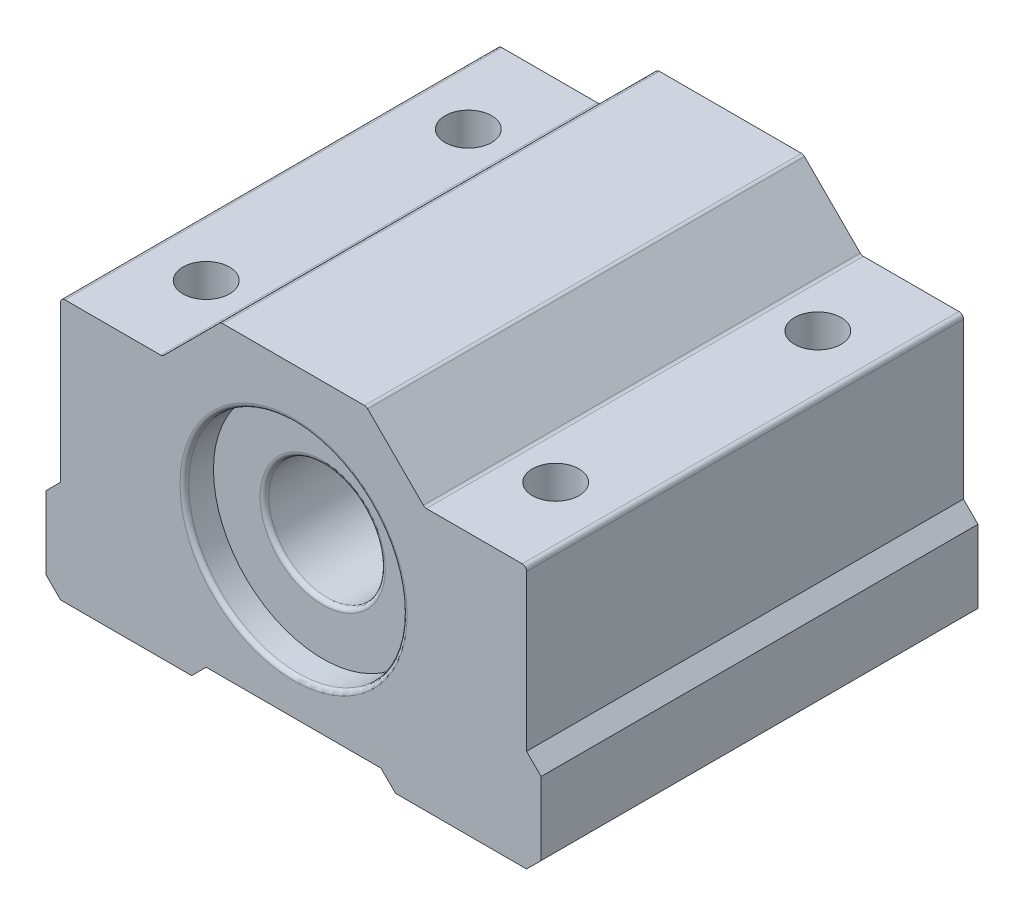
SolidWorks part; units mm, degrees
ref_plane "Front Plane" through (0, 0, 0) normal (0, 0, 1) x (1, 0, 0)
ref_plane "Top Plane" through (0, 0, 0) normal (0, 1, 0) x (1, 0, 0)
ref_plane "Right Plane" through (0, 0, 0) normal (1, 0, 0) x (0, 0, -1)
sketch "Sketch2" plane through (0, 0, 0) normal (0, 0, 1) x (1, 0, 0)
  line L0 (0, 22) -> (0, 0) construction
  line L1 (6, 1) -> (-6, 1)
  line L2 (-6, 1) -> (-7, 0)
  line L3 (6, 1) -> (7, 0)
  line L4 (-7, 0) -> (-17, 0)
  line L5 (7, 0) -> (17, 0)
  line L6 (-17, 0) -> (-17, 6)
  line L7 (17, 0) -> (17, 6)
  line L8 (-17, 6) -> (-16, 7)
  line L9 (17, 6) -> (16, 7)
  line L10 (-16, 7) -> (-16, 18)
  line L11 (16, 7) -> (16, 18)
  line L12 (-16, 18) -> (-9, 18)
  line L13 (16, 18) -> (9, 18)
  line L14 (-9, 18) -> (-5, 22)
  line L15 (9, 18) -> (5, 22)
  line L16 (-5, 22) -> (5, 22)
  circle A0 centre (0, 11) radius 4
  point P6 (0, 1)
  point P20 (0, 22)
  dimension "D10" = 8
  dimension "D1" = 14
  dimension "D2" = 12
  dimension "D3" = 34
  dimension "D4" = 6
  dimension "D5" = 7
  dimension "D6" = 18
  dimension "D7" = 32
  dimension "D8" = 22
  dimension "D9" = 10
  dimension "D11" = 11
extrude "Boss-Extrude1" add sketch "Sketch2" along normal mid plane 30
sketch "Sketch3" plane through (0, 0, -15) normal (0, 0, -1) x (-1, 0, 0)
  circle A0 centre (0, 11) radius 7.5
  dimension "D1" = 15
extrude "Cut-Extrude1" cut sketch "Sketch3" against normal blind 2
mirror "Mirror1" about plane through (0, 0, 0) normal (0, 0, 1) of "Cut-Extrude1"
sketch "Sketch4" plane through (0, 0, 0) normal (0, -1, 0) x (-1, 0, 0)
  line L0 (-12, 12.5594) -> (-12, -12.4986) construction
  line L1 (12, 12.5594) -> (12, -12.4986) construction
  line L2 (-14.6153, -9) -> (-9.7496, -9) construction
  line L3 (0, 14.6882) -> (0, -15) construction
  line L4 (6, -15) -> (-6, -15) construction
  line L5 (14.6153, -9) -> (9.7496, -9) construction
  line L6 (-15.1627, 9) -> (-9.7496, 9) construction
  line L7 (15.1627, 9) -> (9.7496, 9) construction
  line L8 (-15.8671, 0) -> (14.6153, 0) construction
  line L9 (15.8671, 0) -> (-14.6153, 0) construction
  circle A0 centre (-12, 9) radius 1.6
  circle A1 centre (12, 9) radius 1.6
  circle A2 centre (-12, -9) radius 1.6
  circle A3 centre (12, -9) radius 1.6
  point P16 (-12, 9)
  point P17 (12, 9)
  point P18 (-12, -9)
  point P19 (12, -9)
  dimension "D1" = 3.2
  dimension "D2" = 24
  dimension "D3" = 18
extrude "Cut-Extrude2" cut sketch "Sketch4" against normal through all
chamfer "Chamfer1" distance 1 angle 45 2 edges at (17, 0, 0) (-17, 0, 0)
fillet "Fillet1" radius 0.3 10 edges at (-7.5, 11, -15) (-4, 11, -13) (4, 11, 13) (-7.5, 11, 15) (5, 22, 0) (-5, 22, 0) (-9, 18, 0) (9, 18, 0) (16, 18, 0) (-16, 18, 0)
